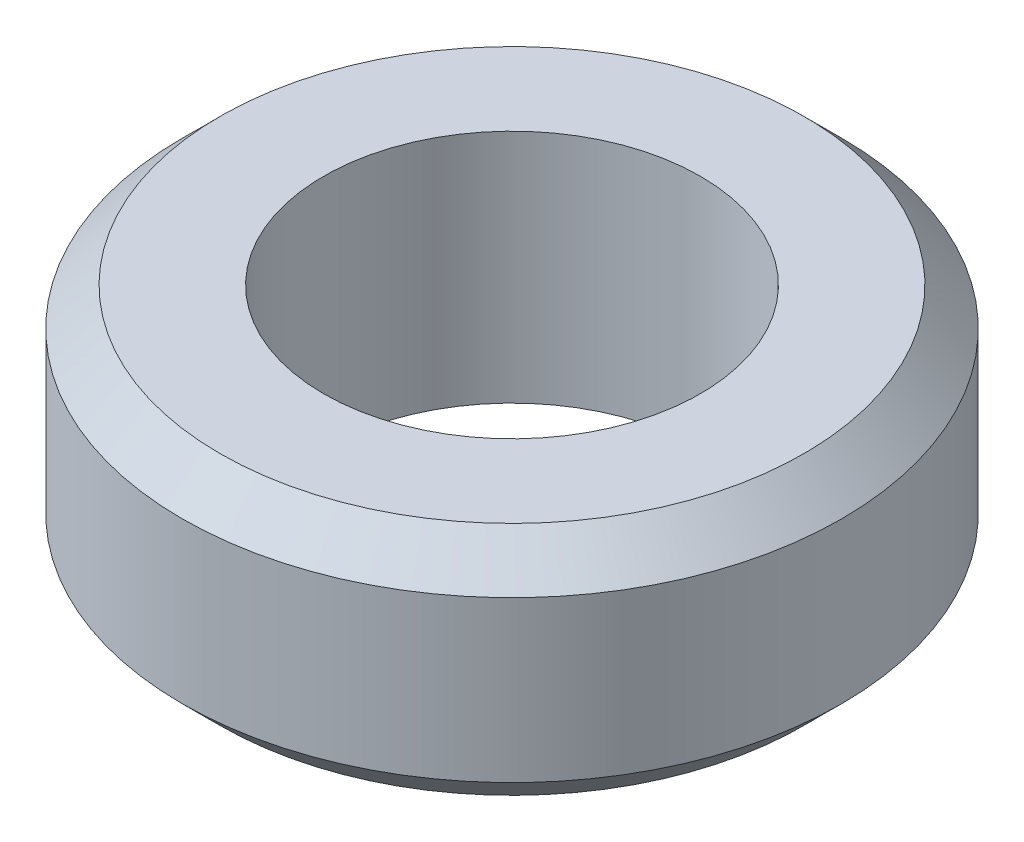
SolidWorks part; units mm, degrees
ref_plane "前视基准面" through (0, 0, 0) normal (0, 0, 1) x (1, 0, 0)
ref_plane "上视基准面" through (0, 0, 0) normal (0, 1, 0) x (1, 0, 0)
ref_plane "右视基准面" through (0, 0, 0) normal (1, 0, 0) x (0, 0, -1)
sketch "草图1" plane through (0, 0, 0) normal (0, 1, 0) x (1, 0, 0)
  circle A0 centre (0, 0) radius 2
  circle A1 centre (0, 0) radius 3.5
  dimension "D1" = 4
  dimension "D2" = 7
extrude "凸台-拉伸1" add sketch "草图1" along normal blind 2.5
chamfer "倒角1" distance 0.4 angle 45 2 edges at (0, 0, 3.5) (0, 2.5, 3.5)
